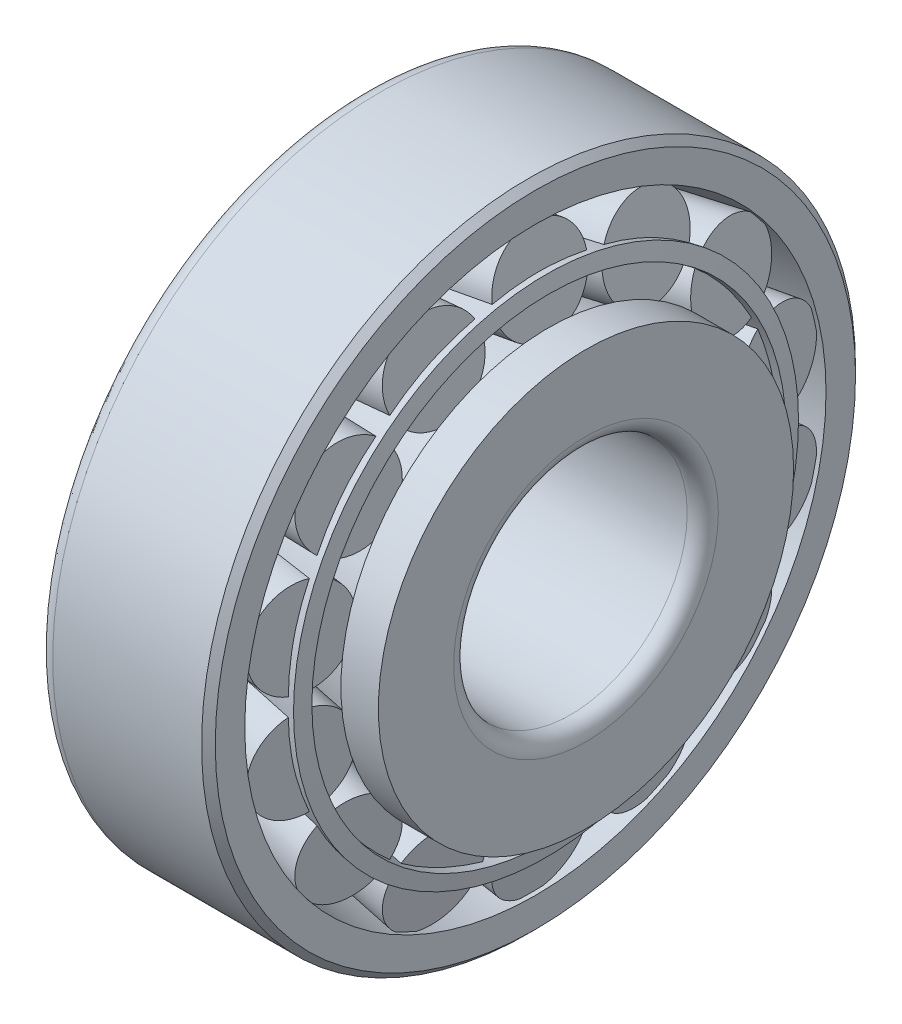
SolidWorks part; units mm, degrees
revolve "OuterRace" add sketch "OutRacSke" angle 360 about L5
sketch "OutRacSke" plane through (0, 0, 0) normal (0, 0, 1) x (1, 0, 0)
  line L0 (-3.25, 18.6648) -> (-14.25, 16.636)
  line L1 (-14.25, 16.636) -> (-14.25, 20)
  line L2 (-13.25, 21) -> (-3.69, 21)
  line L3 (-3.69, 21) -> (-3.25, 20.56)
  line L4 (-3.25, 20.56) -> (-3.25, 18.6648)
  line L5 (-42.5, 0) -> (42.5, 0) construction
  arc A0 (-14.25, 20) -> (-13.25, 21) centre (-13.25, 20) cw
  dimension "cup_radius" = 1
  dimension "OD" = 42
  dimension "cup_width" = 11
  dimension "Tangle" = 10.45
  dimension "offset" = 14.25
  dimension "chamfer" = 0.44
  dimension "D8" = 45
  dimension "cup_SID" = 33.272
ref_plane "Plane1" through (0, 0, 0) normal (0, 0, 1) x (1, 0, 0)
ref_plane "Plane2" through (0, 0, 0) normal (0, 1, 0) x (1, 0, 0)
ref_plane "Plane3" through (0, 0, 0) normal (1, 0, 0) x (0, 0, -1)
sketch "Clipboard" plane through (0, 0, 0) normal (0, 0, 1) x (1, 0, 0)
  line L0 (0, 0) -> (10, 0) construction
  line L1 (0, 0) -> (32.2837, -8.0492)
  line L2 (0, 0) -> (14.9977, -0.2618)
  line L3 (0, 0) -> (41.9936, 0.733)
  line L4 (0, 0) -> (-9.894, -0.3455)
  line L5 (0, 0) -> (-6.075, 14.25)
  dimension "Bore" = 15
  dimension "Count" = 359
  dimension "Show_count" = 359
  dimension "Max_count" = 14
  dimension "Min_count" = 2
  dimension "Race_OD" = 42
  dimension "Race_ID" = 33.272
  dimension "cyl_len" = 9.9
  dimension "Roller_diameter" = 6.075
  dimension "OA_width" = 14.25
sketch "RolDetSke" plane through (0, 0, 0) normal (0, 0, 1) x (1, 0, 0)
  line L0 (-12.6991, 13.9174) -> (-13.25, 16.9045)
  line L1 (-12.6991, 13.9174) -> (-2.9633, 15.7131)
  line L2 (-3.5142, 18.7002) -> (-2.9633, 15.7131)
  line L4 (-38.3072, 9.1943) -> (12.0051, 18.4738) construction
  line L5 (-3.5142, 18.7002) -> (-13.25, 16.9045)
  line L9 (-3.25, 18.6648) -> (-14.25, 16.636) construction
  dimension "cyl_len" = 9.9
  dimension "Roller_diameter" = 6.075
  dimension "dy" = 16.9045
  dimension "D2" = 13.25
revolve "RollerDetailed" add sketch "RolDetSke" angle 360 about L4
sketch "RolSimSke" plane through (0, 0, 0) normal (0, 0, 1) x (1, 0, 0)
  line L0 (0, 0) -> (-32, 0) construction
  line L1 (-13.25, 16.9045) -> (-3.5142, 18.7002)
  line L2 (-13.25, 16.9045) -> (-12.1481, 10.9303)
  line L3 (-12.1481, 10.9303) -> (-2.4123, 12.7259)
  line L4 (-3.5142, 18.7002) -> (-2.4123, 12.7259)
  dimension "Tangle" = 10.45
  dimension "Roller_diameter" = 6.075
  dimension "dy" = 16.9045
  dimension "dx" = 13.25
revolve "RollersSimplified" [suppressed] add sketch "RolSimSke" angle 360 about L0
ref_axis "Axis1" through (-50, 0, 0) along (1, 0, 0)
pattern_circular "RollersDetailed" count 14 every 25.714 about axis through (-50, 0, 0) along (1, 0, 0) of "RollerDetailed"
sketch "InsRacSke" plane through (0, 0, 0) normal (0, 0, 1) x (1, 0, 0)
  line L0 (-12.1986, 11.2341) -> (-13, 11.2341)
  line L1 (-14.25, 20) -> (-14.25, -20) construction
  line L2 (-13, 11.2341) -> (-13, 7.94)
  line L3 (-13, 7.94) -> (-12.56, 7.5)
  line L4 (-12.56, 7.5) -> (-1, 7.5)
  line L5 (0, 8.5) -> (0, 13.3334)
  line L6 (0, 13.3334) -> (-2.4068, 13.3334)
  line L7 (-2.4068, 13.3334) -> (-2.4068, 12.7259)
  line L8 (-2.4068, 12.7259) -> (-12.1426, 10.9303)
  line L9 (-12.1426, 10.9303) -> (-12.1986, 11.2341)
  line L10 (-42.5, 0) -> (42.5, 0) construction
  arc A0 (-1, 7.5) -> (0, 8.5) centre (-1, 8.5) ccw
  dimension "Tangle" = 10.45
  dimension "chamfer" = 0.44
  dimension "Bore" = 15
  dimension "cyl_len" = 9.9
  dimension "dy" = 10.9303
  dimension "dx" = 12.1426
  dimension "D11" = 45
  dimension "D2" = 14.25
revolve "InnerRace" add sketch "InsRacSke" angle 360 about L10
sketch "CagSpiSke" plane through (0, 0, 0) normal (0, 0, 1) x (1, 0, 0)
  line L3 (-2.4765, 15.7187) -> (-12.6991, 13.8333)
  line L4 (-13.0239, 13.3616) -> (-12.877, 12.565)
  line L6 (-42.5, 0) -> (42.5, 0) construction
  arc A1 (-12.6991, 13.8333) -> (-13.0239, 13.3616) centre (-12.6256, 13.435) ccw
  dimension "Tangle" = 10.45
  dimension "radius" = 0.405
  dimension "dx" = 12.6991
  dimension "dy" = 13.8333
  dimension "offset" = 1.215
revolve "CageSpine" add sketch "CagSpiSke" angle 360 about L6
equation "\"OD@OutRacSke\" = \"Race_OD@Clipboard\""
equation "\"cup_SID@OutRacSke\" = \"Race_ID@Clipboard\""
equation "\"chamfer@OutRacSke\" = \"cup_width@OutRacSke\" / 25"
equation "\"offset@OutRacSke\" = \"OA_width@Clipboard\""
equation "\"D2@RolDetSke\" = \"offset@OutRacSke\" - \"cup_radius@OutRacSke\""
equation "\"dy@RolDetSke\" =  ( ( \"Race_ID@Clipboard\" / 2 ) + ( \"cup_radius@OutRacSke\" ) * tan(\"Tangle@OutRacSke\" * 3.141592654/180) ) * 1.005"
equation "\"cyl_len@RolDetSke\" = \"cyl_len@Clipboard\""
equation "\"Roller_diameter@RolDetSke\" = \"Roller_diameter@Clipboard\""
equation "\"dx@RolSimSke\" = \"offset@OutRacSke\" - \"cup_radius@OutRacSke\""
equation "\"dy@RolSimSke\" =  ( ( \"Race_ID@Clipboard\" / 2 ) + ( \"cup_radius@OutRacSke\" ) * tan(\"Tangle@OutRacSke\" * 3.141592654/180) ) * 1.005"
equation "\"Cyl_Len@RolSimSke\" = \"cyl_len@Clipboard\""
equation "\"Roller_diameter@RolSimSke\" = \"Roller_diameter@Clipboard\""
equation "\"Bore@InsRacSke\" = \"Bore@Clipboard\""
equation "\"Tangle@InsRacSke\" = \"Tangle@OutRacSke\""
equation "\"cyl_len@InsRacSke\" = \"cyl_len@Clipboard\""
equation "\"chamfer@InsRacSke\" = \"chamfer@OutRacSke\""
equation "\"D2@InsRacSke\" = \"OA_width@Clipboard\""
equation "\"dx@InsRacSke\" = \"offset@OutRacSke\" - \"cup_radius@OutRacSke\" -  (  \"Roller_diameter@Clipboard\" * 1.005 )  * sin(\"Tangle@InsRacSke\" * 3.141592654/180)"
equation "\"dy@InsRacSke\" = ( ( \"Race_ID@Clipboard\" / 2 ) + ( \"cup_radius@OutRacSke\" ) * tan(\"Tangle@OutRacSke\" * 3.141592654/180) ) * 1.005 -  ( \"Roller_diameter@Clipboard\" )  * cos(\"Tangle@InsRacSke\" * 3.141592654/180) "
equation "\"front_groove@InsRacSke\" = \"Groove_dp@InsRacSke\" / 2"
equation "\"Tangle@CagSpiSke\" = \"Tangle@OutRacSke\""
equation "\"dx@CagSpiSke\" = ( \"offset@OutRacSke\" - \"cup_radius@OutRacSke\" ) -  (  \"Roller_diameter@Clipboard\" / 2  )  * sin(\"Tangle@InsRacSke\" * 3.141592654/180)"
equation "\"dy@CagSpiSke\" = ( ( \"Race_ID@Clipboard\" / 2 ) + ( \"cup_radius@OutRacSke\" ) * tan(\"Tangle@OutRacSke\" * 3.141592654/180) )  -  ( \"Roller_diameter@Clipboard\" / 2 )  * cos(\"Tangle@InsRacSke\" * 3.141592654/180) "
equation "\"length@CagSpiSke\" = \"cyl_len@Clipboard\" * 1.05"
equation "\"offset@CagSpiSke\" = \"Roller_diameter@Clipboard\" / 5"
equation "\"radius@CagSpiSke\" = \"offset@CagSpiSke\" / 3"
equation "\"D3@CageSpine\" = \"Roller_diameter@Clipboard\" / 6"
equation "\"Max_count@Clipboard\" = int( 3.14159265 / atn(( \"Roller_diameter@Clipboard\" / 2) / sqr( \"dy@CagSpiSke\"  *  \"dy@CagSpiSke\" - ( \"Roller_diameter@Clipboard\" / 2) *  ( \"Roller_diameter@Clipboard\" / 2))))"
equation "\"Max_count@Clipboard\" = ((sgn( \"Max_count@Clipboard\" - \"Count@Clipboard\" )-1)*( \"Max_count@Clipboard\" - \"Count@Clipboard\" ))/-2+ \"Count@Clipboard\""
equation "\"Count@RollersDetailed\" = int( \"Show_count@Clipboard\" ) "
equation "\"Count@RollersDetailed\" = ((sgn( \"Count@RollersDetailed\" - \"Max_count@Clipboard\" )-1)*( \"Count@RollersDetailed\" - \"Max_count@Clipboard\" ))/-2+ \"Max_count@Clipboard\""
equation "\"Count@RollersDetailed\" = ((sgn( \"Count@RollersDetailed\" - \"Min_count@Clipboard\" )+1)*( \"Count@RollersDetailed\" - \"Min_count@Clipboard\"))/2 +\"Min_count@Clipboard\""
equation "\"Angle@RollersDetailed\" = 360.0 / \"Max_count@Clipboard\""
equation "\"Angle@CageSpine\" =  \"Angle@RollersDetailed\" * ( \"Count@RollersDetailed\" -1 + int( \"Count@RollersDetailed\" / \"Max_count@Clipboard\" ) )  + 0.001 -  int( \"Count@RollersDetailed\" / \"Max_count@Clipboard\" ) * 0.001"
equation "\"Angle@CageSpine\" =  \"Angle@CageSpine\" * int( \"Min_count@Clipboard\" / 2) + int(1 / \"Min_count@Clipboard\")  * 0.001"
equation "\"Tangle@RolSimSke\" = \"Tangle@OutRacSke\""
